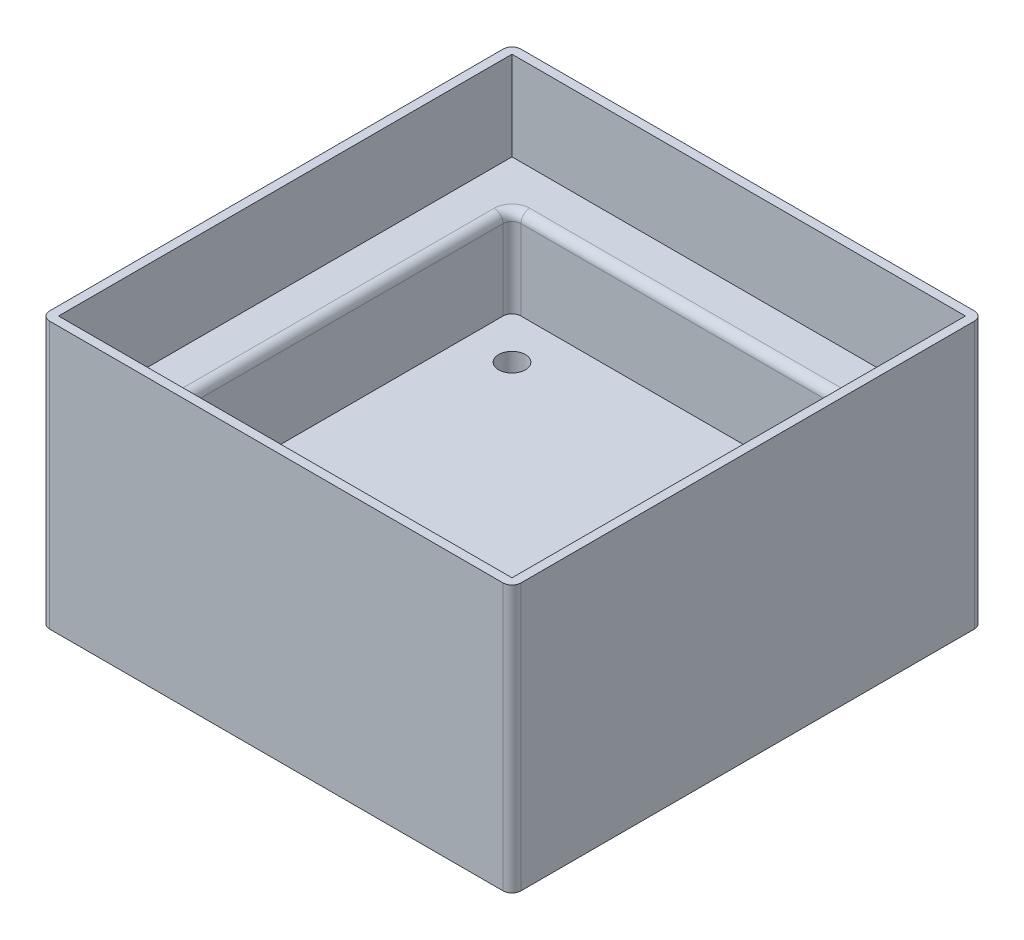
SolidWorks part; units mm, degrees
ref_plane "Front Plane" through (0, 0, 0) normal (0, 0, 1) x (1, 0, 0)
ref_plane "Top Plane" through (0, 0, 0) normal (0, 1, 0) x (1, 0, 0)
ref_plane "Right Plane" through (0, 0, 0) normal (1, 0, 0) x (0, 0, -1)
sketch "Sketch1" plane through (0, 0, 0) normal (0, 1, 0) x (1, 0, 0)
  line L1 (0, 0) -> (53, 0)
  line L2 (0, 0) -> (0, -53)
  line L3 (0, -53) -> (53, -53)
  line L4 (53, 0) -> (53, -53)
  dimension "D1" = 53
  dimension "D2" = 53
extrude "Boss-Extrude1" add sketch "Sketch1" along normal blind 30
sketch "Sketch6" plane through (0, 30, 0) normal (0, 1, 0) x (1, 0, 0)
  line L0 (0, 0) -> (0, -53) construction
  line L1 (1, -1) -> (52, -1)
  line L2 (1, -1) -> (1, -52)
  line L3 (1, -52) -> (52, -52)
  line L4 (52, -1) -> (52, -52)
  line L5 (53, -53) -> (53, 0) construction
  line L6 (53, 0) -> (0, 0) construction
  line L7 (0, -53) -> (53, -53) construction
  dimension "D1" = 1
  dimension "D2" = 1
  dimension "D3" = 1
  dimension "D4" = 1
extrude "Cut-Extrude1" cut sketch "Sketch6" against normal blind 10
sketch "Sketch7" plane through (0, 20, 0) normal (0, 1, 0) x (1, 0, 0)
  line L8 (6, -6) -> (6, -47)
  line L9 (6, -47) -> (47, -47)
  line L10 (47, -47) -> (47, -6)
  line L11 (47, -6) -> (6, -6)
  line L12 (6, -6) -> (6, -47)
  line L13 (6, -47) -> (47, -47)
  line L14 (47, -47) -> (47, -6)
  line L15 (47, -6) -> (6, -6)
  dimension "D1" = 5
extrude "Cut-Extrude2" cut sketch "Sketch7" against normal blind 10
sketch "Sketch13" plane through (0, 10, 0) normal (0, 1, 0) x (1, 0, 0)
  line L12 (42, -11) -> (11, -11)
  line L13 (11, -11) -> (11, -42)
  line L14 (11, -42) -> (42, -42)
  line L15 (42, -42) -> (42, -11)
  dimension "D1" = 31
  dimension "D2" = 31
sketch "Sketch14" plane through (0, 10, 0) normal (0, 1, 0) x (1, 0, 0)
  circle A0 centre (11, -11) radius 1.5
  circle A1 centre (42, -11) radius 1.5
  circle A2 centre (42, -42) radius 1.5
  circle A3 centre (11, -42) radius 1.5
  dimension "D1" = 3
  dimension "D2" = 3
  dimension "D3" = 3
  dimension "D4" = 3
extrude "Cut-Extrude4" cut sketch "Sketch14" against normal through all
fillet "Fillet1" radius 1 12 edges at (0, 15, 0) (0, 15, 53) (53, 15, 0) (53, 15, 53) (6, 15, 47) (47, 15, 47) (47, 15, 6) (6, 15, 6) (26.5, 20, 47) (47, 20, 26.5) (6, 20, 26.5) (26.5, 20, 6)
equation "\"D2@Sketch1\"=\"D1@Sketch1\""
equation "\"D2@Sketch6\"=\"D1@Sketch6\""
equation "\"D3@Sketch6\"=\"D1@Sketch6\""
equation "\"D4@Sketch6\"=\"D1@Sketch6\""
equation "\"D1@Cut-Extrude1\"=\"D1@Sketch6\""
equation "\"D2@Sketch13\"=\"D1@Sketch13\""
equation "\"D2@Sketch14\"=\"D1@Sketch14\""
equation "\"D3@Sketch14\"=\"D1@Sketch14\""
equation "\"D4@Sketch14\"=\"D1@Sketch14\""
